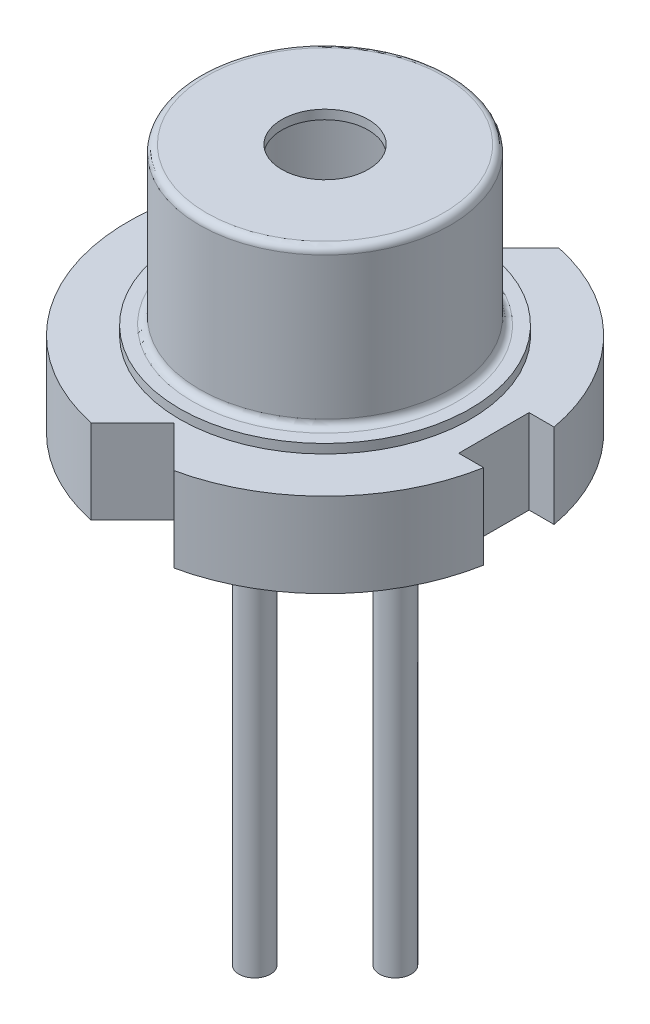
SolidWorks part; units mm, degrees
ref_plane "Front Plane" through (0, 0, 0) normal (0, 0, 1) x (1, 0, 0)
ref_plane "Top Plane" through (0, 0, 0) normal (0, 1, 0) x (1, 0, 0)
ref_plane "Right Plane" through (0, 0, 0) normal (1, 0, 0) x (0, 0, -1)
sketch "Sketch1" plane through (0, 0, 0) normal (0, 1, 0) x (1, 0, 0)
  circle A0 centre (0, 0) radius 2.8
  dimension "D1" = 5.6
extrude "Boss-Extrude1" add sketch "Sketch1" along normal blind 1.2
sketch "Sketch2" plane through (0, 1.2, 0) normal (0, 1, 0) x (1, 0, 0)
  circle A0 centre (0, 0) radius 2.065
  dimension "D1" = 4.13
extrude "Boss-Extrude2" add sketch "Sketch2" along normal blind 0.13
sketch "Sketch3" plane through (0, 1.33, 0) normal (0, 1, 0) x (1, 0, 0)
  circle A0 centre (0, 0) radius 1.785
  dimension "D1" = 3.57
extrude "Boss-Extrude3" add sketch "Sketch3" along normal blind 2.22
sketch "Sketch4" plane through (0, 3.55, 0) normal (0, 1, 0) x (1, 0, 0)
  circle A0 centre (0, 0) radius 0.615
  dimension "D1" = 1.23
extrude "Cut-Extrude1" cut sketch "Sketch4" against normal blind 1
sketch "Sketch5" plane through (0, 0, 0) normal (0, -1, 0) x (1, 0, 0)
  circle A0 centre (0, 1) radius 0.4
  circle A1 centre (0, -1) radius 0.4
  dimension "D1" = 0.8
  dimension "D2" = 0.8
  dimension "D4" = 2
  dimension "D5" = 1
extrude "Boss-Extrude4" add sketch "Sketch5" along normal blind 0.05
sketch "Sketch6" plane through (0, 0, 0) normal (0, -1, 0) x (1, 0, 0)
  line L0 (0, 2.15) -> (0.65, 2.8)
  line L1 (2.8, 0.5) -> (2.4, 0.5)
  line L2 (2.8, 0.5) -> (2.8, -0.5)
  line L3 (2.8, -0.5) -> (2.4, -0.5)
  line L4 (2.4, 0.5) -> (2.4, -0.5)
  line L5 (0.65, 2.8) -> (-0.65, 2.8)
  line L6 (-0.65, 2.8) -> (0, 2.15)
  line L7 (0, -2.15) -> (-0.65, -2.8)
  line L8 (-0.65, -2.8) -> (0.65, -2.8)
  line L9 (0.65, -2.8) -> (0, -2.15)
  circle A0 centre (0, 0) radius 2.8 construction
  point P4 (2.8, 0)
  point P7 (2.4, 0)
  point P11 (0, 2.8)
  dimension "D1" = 2.8
  dimension "D2" = 2.4
  dimension "D3" = 0
  dimension "D4" = 1
  dimension "D5" = 2.8
  dimension "D6" = 0.65
  dimension "D7" = 0.65
  dimension "D8" = 2.8
  dimension "D9" = 45
  dimension "D10" = 0
extrude "Cut-Extrude2" cut sketch "Sketch6" against normal through all
sketch "Sketch7" plane through (0, 0, 0) normal (0, -1, 0) x (1, 0, 0)
  circle A0 centre (1, 0) radius 0.6
  dimension "D2" = 1.2
  dimension "D1" = 1
extrude "Boss-Extrude5" add sketch "Sketch7" along normal blind 0.4
sketch "Sketch8" plane through (0, -0.05, 0) normal (0, -1, 0) x (1, 0, 0)
  circle A0 centre (0, 1) radius 0.225
  circle A1 centre (0, -1) radius 0.225
  circle A2 centre (1, 0) radius 0.225
  circle A3 centre (0, -1) radius 0.4 construction
  circle A4 centre (1, 0) radius 0.6 construction
  circle A5 centre (0, 1) radius 0.4 construction
  dimension "D1" = 0.45
  dimension "D2" = 0.45
  dimension "D3" = 0.45
  dimension "D5" = 0
  dimension "D6" = 0
  dimension "D4" = 0
extrude "Boss-Extrude6" add sketch "Sketch8" along normal blind 6
fillet "Fillet1" radius 0.1 2 edges at (0, 1.33, 1.785) (0, 3.55, 1.785)
sketch "Sketch9" plane through (0, 1.2, 0) normal (0, 1, 0) x (1, 0, 0)
  circle A0 centre (0, 0) radius 1.655
  circle A1 centre (0, 0) radius 1.785 construction
  dimension "D1" = 0.13
extrude "Cut-Extrude3" cut sketch "Sketch9" along normal blind 2.22
sketch "Sketch11" [suppressed] plane through (0, 1.2, 0) normal (0, 1, 0) x (1, 0, 0)
  line L0 (-0.4, 0.6) -> (-0.4, -0.6)
  line L1 (-0.4, 0.6) -> (-0.6, 0.6)
  line L2 (-0.6, 0.6) -> (-0.6, 1.3584)
  line L3 (-0.4, -0.6) -> (-0.6, -0.6)
  line L4 (-0.6, -0.6) -> (-0.6, -1.3584)
  circle A0 centre (0, 1) radius 0.225
  circle A1 centre (0, -1) radius 0.225
  circle A2 centre (0, 1) radius 0.4 construction
  circle A3 centre (0, -1) radius 0.225 construction
  arc A4 (-0.6, 1.3584) -> (-0.6, -1.3584) centre (0, 0) ccw
  circle A5 centre (0, 0) radius 1.685 construction
  dimension "D1" = 0
  dimension "D2" = 0
  dimension "D3" = 0.45
  dimension "D4" = 0.45
  dimension "D5" = 0.2
  dimension "D6" = 0.4
  dimension "D7" = 0.2
  dimension "D8" = 0.6
  dimension "D9" = 0.2
  dimension "D10" = 0.6
extrude "Boss-Extrude8" [suppressed] add sketch "Sketch11" along normal blind 1.6
sketch "Sketch12" [suppressed] plane through (-0.4, 0, 0) normal (1, 0, 0) x (0, 0, -1)
  line L0 (-0.6, 1.2) -> (0.6, 1.2) construction
  line L1 (-0.4, 2.75) -> (0.5, 2.75)
  line L2 (-0.4, 2.75) -> (-0.4, 1.3)
  line L3 (-0.4, 1.3) -> (0.5, 1.3)
  line L4 (0.5, 2.75) -> (0.5, 1.3)
  line L5 (-0.6, 2.8) -> (0.6, 2.8) construction
  line L6 (0.6, 2.8) -> (0.6, 1.2) construction
  dimension "D1" = 0.1
  dimension "D2" = 0.05
  dimension "D3" = 0.9
  dimension "D4" = 0.1
extrude "Boss-Extrude9" [suppressed] add sketch "Sketch12" along normal blind 0.25
sketch "Sketch13" [suppressed] plane through (0, 3.42, 0) normal (0, -1, 0) x (1, 0, 0)
  circle A0 centre (0, 0) radius 0.9
  dimension "D1" = 1.8
extrude "Boss-Extrude10" [suppressed] add sketch "Sketch13" along normal blind 0.15
